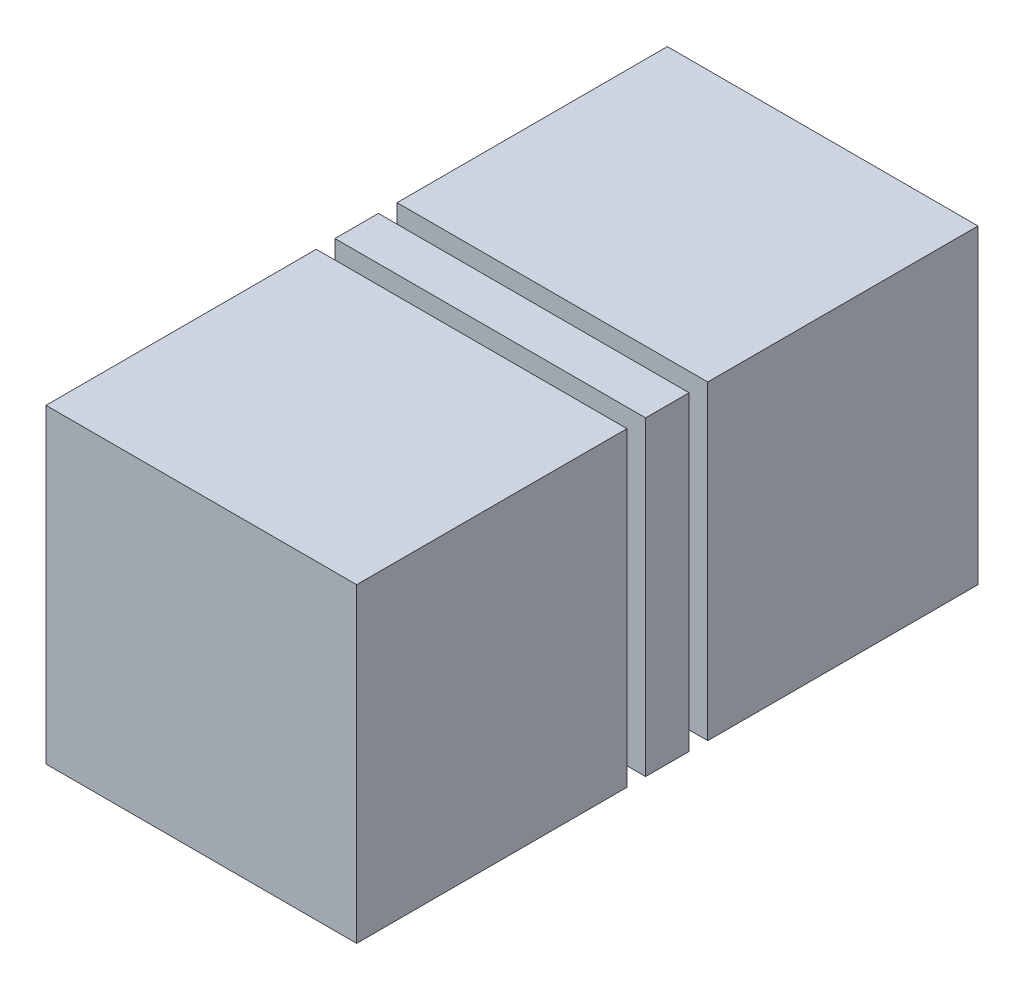
SolidWorks part; units mm, degrees
ref_plane "Front Plane" through (0, 0, 0) normal (0, 0, 1) x (1, 0, 0)
ref_plane "Top Plane" through (0, 0, 0) normal (0, 1, 0) x (1, 0, 0)
ref_plane "Right Plane" through (0, 0, 0) normal (1, 0, 0) x (0, 0, -1)
sketch "Sketch1" plane through (0, 0, 0) normal (1, 0, 0) x (0, 0, -1)
  line L1 (50, -25) -> (-50, -25)
  line L2 (50, -25) -> (50, 25)
  line L3 (50, 25) -> (-50, 25)
  line L4 (-50, -25) -> (-50, 25)
  line L5 (50, -25) -> (-50, 25) construction
  line L6 (50, 25) -> (-50, -25) construction
  point P0 (0, 0)
  dimension "D1" = 50
  dimension "D2" = 100
extrude "Boss-Extrude1" add sketch "Sketch1" along normal mid plane 50
ref_plane "Plane1" through (0, 0, 5) normal (0, 0, 1) x (1, 0, 0)
sketch "Sketch2" plane through (0, 0, 5) normal (0, 0, 1) x (1, 0, 0)
  line L10 (25, -25) -> (-25, -25) construction
  line L11 (25, 25) -> (25, -25) construction
  line L12 (25, 25) -> (-25, 25) construction
  line L13 (-25, 25) -> (-25, -25) construction
  line L14 (-22, 22) -> (-22, -22)
  line L15 (-22, -22) -> (22, -22)
  line L16 (22, -22) -> (22, 22)
  line L17 (22, 22) -> (-22, 22)
  line L18 (-22, 22) -> (-22, -22)
  line L19 (-22, -22) -> (22, -22)
  line L20 (22, -22) -> (22, 22)
  line L21 (22, 22) -> (-22, 22)
  line L22 (25, -25) -> (-25, -25)
  line L23 (25, 25) -> (25, -25)
  line L24 (25, 25) -> (-25, 25)
  line L25 (-25, 25) -> (-25, -25)
  dimension "D1" = 3
extrude "Cut-Extrude1" cut sketch "Sketch2" against normal mid plane 3
mirror "Mirror1" about plane through (0, 0, 0) normal (0, 0, 1) of "Cut-Extrude1"
